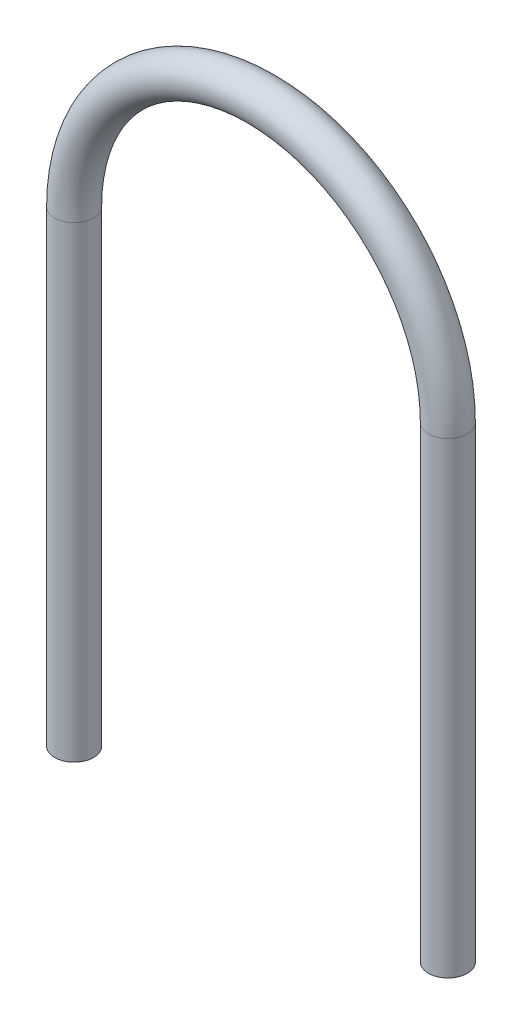
SolidWorks part; units mm, degrees
material "AISI 1020"
ref_plane "Front Plane" through (0, 0, 0) normal (0, 0, 1) x (1, 0, 0)
ref_plane "Top Plane" through (0, 0, 0) normal (0, 1, 0) x (1, 0, 0)
ref_plane "Right Plane" through (0, 0, 0) normal (1, 0, 0) x (0, 0, -1)
sketch "Sketch1" plane through (0, 0, 0) normal (0, 0, 1) x (1, 0, 0)
  line L0 (0, 0) -> (0, 76.2)
  line L1 (-54.61, 76.2) -> (-54.61, 0)
  arc A0 (0, 76.2) -> (-54.61, 76.2) centre (-27.305, 76.2) ccw
  dimension "D1" = 27.305
sketch "Sketch2" plane through (0, 0, 0) normal (0, 1, 0) x (1, 0, 0)
  line L0 (0, 0) -> (3.175, 0) construction
  circle A0 centre (3.175, 0) radius 3.175
  dimension "D1" = 6.35
sweep "Sweep1" add profiles "Sketch2" path "Sketch1"
ref_plane "Plane1" through (0, 76.2, 0) normal (0, -1, 0) x (1, 0, 0)
sketch "Sketch3" plane through (0, 76.2, 0) normal (0, -1, 0) x (1, 0, 0)
  line L0 (0, 0) -> (0, -2.2894)
  line L1 (0, -2.2894) -> (0.1416, -2.2894)
  line L2 (0.1416, -2.2894) -> (0.1416, 2.0391)
  line L3 (0.1416, 2.0391) -> (0, 2.0391)
  line L4 (0, 2.0391) -> (0, 0)
